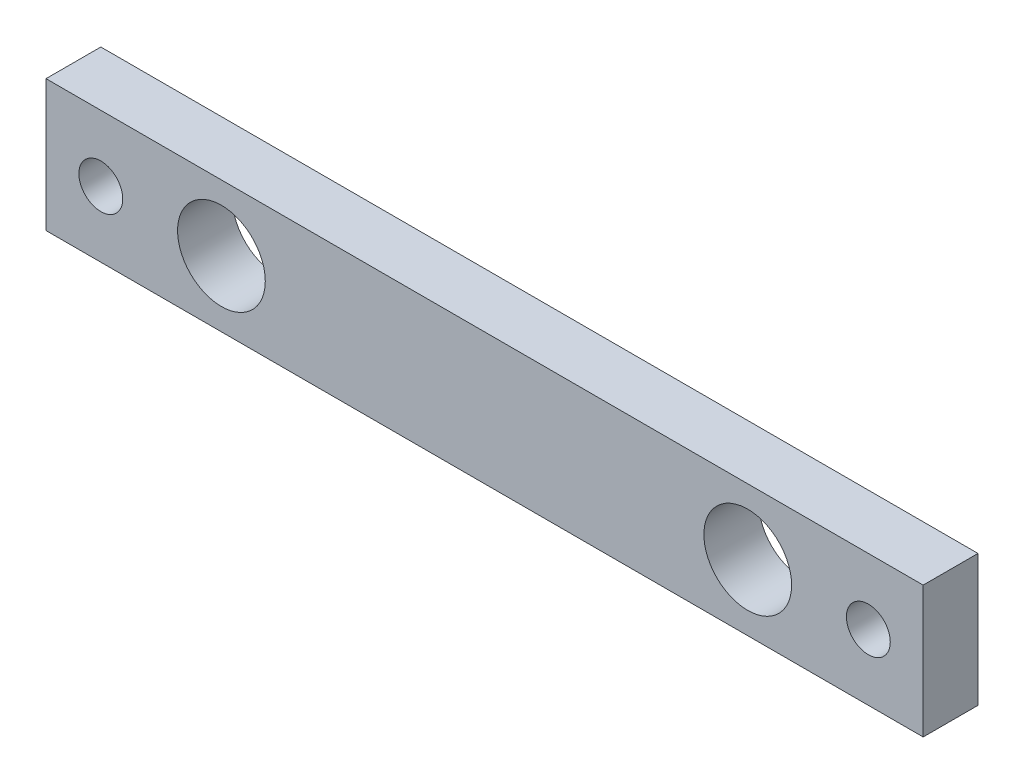
SolidWorks part; units mm, degrees
ref_plane "Front Plane" through (0, 0, 0) normal (0, 0, 1) x (1, 0, 0)
ref_plane "Top Plane" through (0, 0, 0) normal (0, 1, 0) x (1, 0, 0)
ref_plane "Right Plane" through (0, 0, 0) normal (1, 0, 0) x (0, 0, -1)
sketch "Sketch1" plane through (0, 0, 0) normal (0, 0, 1) x (1, 0, 0)
  line L0 (-50, 6) -> (-50, -6)
  line L5 (30, -6) -> (30, 6)
  line L6 (30, 6) -> (-50, 6)
  line L9 (-50, -6) -> (30, -6)
  circle A0 centre (-34, 0) radius 4
  circle A2 centre (14, 0) radius 4
  circle A3 centre (-45, 0) radius 2
  circle A4 centre (25, 0) radius 2
  point P12 (0, 0)
  dimension "D10" = 8
  dimension "D9" = 8
  dimension "D8" = 4
  dimension "D13" = 4
  dimension "D2" = 12
  dimension "D3" = 6
  dimension "D4" = 80
  dimension "D5" = 30
  dimension "D6" = 6
  dimension "D7" = 16
  dimension "D11" = 48
  dimension "D12" = 5
  dimension "D14" = 70
  dimension "D15" = 6
extrude "Boss-Extrude1" add sketch "Sketch1" along normal blind 5
